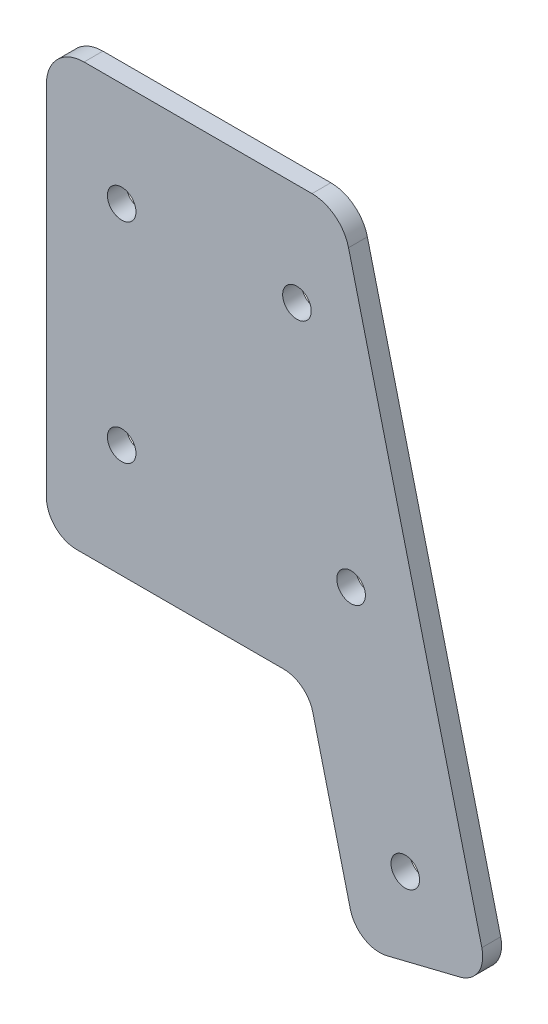
SolidWorks part; units mm, degrees
ref_plane "Front Plane" through (0, 0, 0) normal (0, 0, 1) x (1, 0, 0)
ref_plane "Top Plane" through (0, 0, 0) normal (0, 1, 0) x (1, 0, 0)
ref_plane "Right Plane" through (0, 0, 0) normal (1, 0, 0) x (0, 0, -1)
sketch "Sketch1" plane through (0, 0, 0) normal (0, 0, 1) x (1, 0, 0)
  line L0 (48.5109, 121.8313) -> (71.0064, 30.7949)
  line L2 (-2.4658, 59.8665) -> (-2.4658, 120.308)
  line L3 (3.8842, 126.658) -> (42.3463, 126.658)
  line L9 (48.8139, 25.311) -> (42.4845, 50.9251)
  line L10 (37.5529, 54.7865) -> (2.6142, 54.7865)
  line L11 (54.9642, 21.598) -> (67.2934, 24.6446)
  arc A5 (48.5109, 121.8313) -> (42.3463, 126.658) centre (42.3463, 120.308) ccw
  arc A6 (-2.4658, 120.308) -> (3.8842, 126.658) centre (3.8842, 120.308) cw
  arc A7 (37.5529, 54.7865) -> (42.4845, 50.9251) centre (37.5529, 49.7065) cw
  arc A8 (2.6142, 54.7865) -> (-2.4658, 59.8665) centre (2.6142, 59.8665) cw
  arc A9 (71.0064, 30.7949) -> (67.2934, 24.6446) centre (66.0747, 29.5763) cw
  arc A10 (54.9642, 21.598) -> (48.8139, 25.311) centre (53.7456, 26.5297) cw
  point P11 (43.986, 34.2607)
  point P19 (59.219, -27.3851)
  point P22 (83.8773, -21.2919)
  point P25 (47.3182, 126.658)
  point P28 (-2.4658, 126.658)
  dimension "D9" = 5.08
  dimension "D10" = 22.86
  dimension "D5" = 5.08
  dimension "D1" = 49.784
  dimension "D2" = 103.88
  dimension "D3" = 152.4
  dimension "D4" = 25.4
  dimension "D6" = 63.5
extrude "Boss-Extrude1" add sketch "Sketch1" along normal blind 3.175
sketch "Sketch2" plane through (0, 0, 3.175) normal (0, 0, 1) x (1, 0, 0)
  line L0 (54.9642, 21.598) -> (67.2934, 24.6446) construction
  line L1 (42.3463, 126.658) -> (3.8842, 126.658) construction
  line L2 (-2.4658, 120.308) -> (-2.4658, 59.8665) construction
  line L3 (2.6142, 54.7865) -> (37.5529, 54.7865) construction
  line L4 (71.0064, 30.7949) -> (48.5109, 121.8313) construction
  circle A0 centre (58.0822, 35.4505) radius 2.413
  circle A1 centre (48.9424, 72.438) radius 2.413
  circle A2 centre (39.8026, 109.4255) radius 2.413
  circle A3 centre (10.2342, 109.132) radius 2.413
  circle A4 centre (10.2342, 73.8365) radius 2.413
  dimension "D1" = 4.826
  dimension "D2" = 12.7
  dimension "D3" = 4.826
  dimension "D4" = 38.1
  dimension "D5" = 4.826
  dimension "D6" = 38.1
  dimension "D7" = 4.826
  dimension "D8" = 17.526
  dimension "D9" = 12.7
  dimension "D10" = 4.826
  dimension "D11" = 19.05
  dimension "D12" = 12.7
  dimension "D13" = 11.43
extrude "Cut-Extrude1" cut sketch "Sketch2" against normal through all
